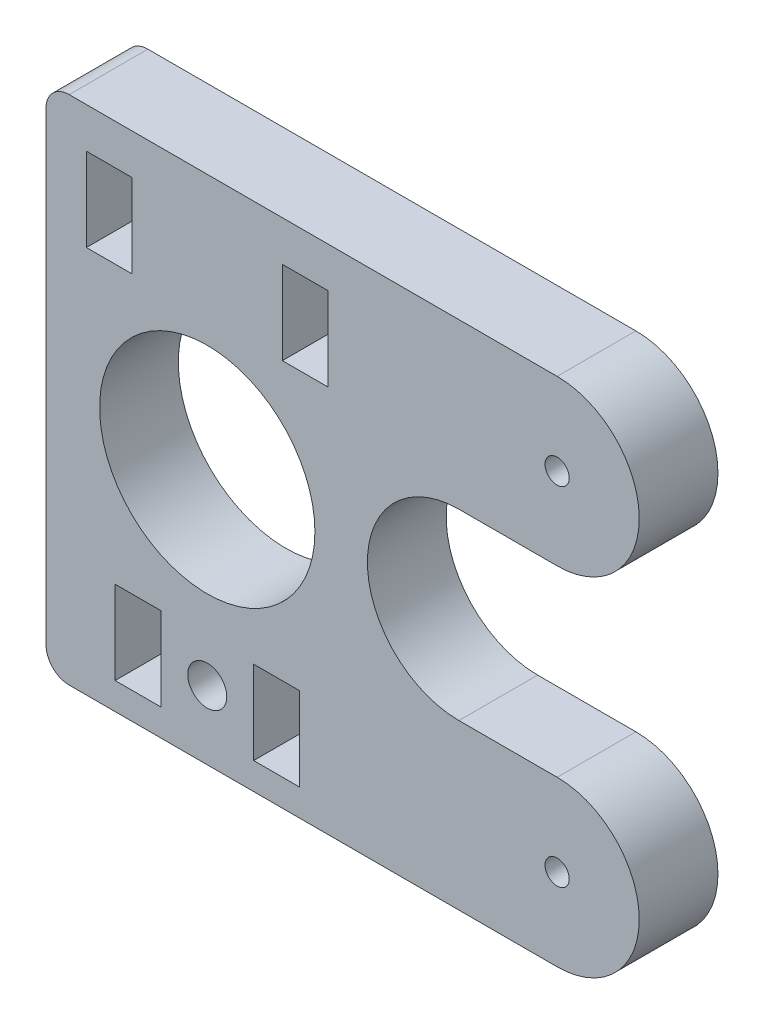
SolidWorks part; units mm, degrees
material "Acrylic (Medium-high impact)"
ref_plane "Front Plane" through (0, 0, 0) normal (0, 0, 1) x (1, 0, 0)
ref_plane "Top Plane" through (0, 0, 0) normal (0, 1, 0) x (1, 0, 0)
ref_plane "Right Plane" through (0, 0, 0) normal (1, 0, 0) x (0, 0, -1)
sketch "Sketch1" plane through (0, 0, 0) normal (0, 0, 1) x (1, 0, 0)
  line L0 (669.2168, 349.7655) -> (648.4638, 349.7655)
  line L1 (646.7465, 348.0482) -> (646.7465, 313.4828)
  line L2 (648.4638, 311.7655) -> (669.2168, 311.7655)
  line L3 (653.1465, 340.5655) -> (653.1465, 346.7655)
  line L4 (653.1465, 346.7655) -> (649.7465, 346.7655)
  line L5 (649.7465, 346.7655) -> (649.7465, 340.5655)
  line L6 (649.7465, 340.5655) -> (653.1465, 340.5655)
  line L7 (651.8765, 313.7655) -> (655.2765, 313.7655)
  line L8 (655.2765, 313.7655) -> (655.2765, 319.9655)
  line L9 (655.2765, 319.9655) -> (651.8765, 319.9655)
  line L10 (651.8765, 319.9655) -> (651.8765, 313.7655)
  line L11 (667.7065, 340.5655) -> (667.7065, 346.7655)
  line L12 (667.7065, 346.7655) -> (664.3065, 346.7655)
  line L13 (664.3065, 346.7655) -> (664.3065, 340.5655)
  line L14 (664.3065, 340.5655) -> (667.7065, 340.5655)
  line L15 (662.1765, 319.9655) -> (662.1765, 313.7655)
  line L16 (662.1765, 313.7655) -> (665.5765, 313.7655)
  line L17 (665.5765, 313.7655) -> (665.5765, 319.9655)
  line L18 (665.5765, 319.9655) -> (662.1765, 319.9655)
  line L19 (-318.4867, 330.7655) -> (49681.5133, 330.7655) construction
  line L21 (653.1465, 340.5655) -> (664.3065, 340.5655) construction
  line L22 (657.2765, 316.8655) -> (655.2765, 316.8655) construction
  line L23 (660.1765, 316.8655) -> (662.1765, 316.8655) construction
  line L24 (658.7265, -666.0306) -> (658.7265, 49333.9694) construction
  line L25 (669.2168, 311.7655) -> (684.7265, 311.7655)
  line L26 (669.2168, 349.7655) -> (684.7265, 349.7655)
  line L27 (684.7265, 317.8655) -> (684.7265, 330.7655) construction
  line L28 (684.7265, 330.7655) -> (684.7265, 343.6655) construction
  line L29 (684.7265, -670.5722) -> (684.7265, 49329.4278) construction
  line L30 (662.1765, 330.7655) -> (662.1765, 349.7655) construction
  line L31 (662.1765, 330.7655) -> (662.1765, 311.7655) construction
  line L32 (684.7265, 337.5655) -> (677.4265, 337.5655)
  line L33 (684.7265, 323.9655) -> (677.4265, 323.9655)
  circle A0 centre (684.7265, 343.6655) radius 0.9
  circle A1 centre (684.7265, 317.8655) radius 0.9
  arc A2 (684.7265, 311.7655) -> (684.7265, 323.9655) centre (684.7265, 317.8655) ccw
  circle A3 centre (658.7265, 316.8655) radius 1.45
  arc A4 (648.4638, 349.7655) -> (646.7465, 348.0482) centre (648.4638, 348.0482) ccw
  arc A5 (684.7265, 349.7655) -> (684.7265, 337.5655) centre (684.7265, 343.6655) cw
  arc A6 (677.4265, 337.5655) -> (677.4265, 323.9655) centre (677.4265, 330.7655) ccw
  arc A7 (646.7465, 313.4828) -> (648.4638, 311.7655) centre (648.4638, 313.4828) ccw
  circle A8 centre (658.7265, 330.7655) radius 8
  point P27 (658.7265, 340.5655)
  point P38 (670.6265, 330.7655)
  point P39 (666.7265, 330.7655)
  dimension "D5" = 2.9
  dimension "D12" = 26
  dimension "D13" = 16
  dimension "D14" = 1.8
  dimension "D15" = 1.7173
  dimension "D1" = 2
  dimension "D2" = 6.2
  dimension "D3" = 3.4
  dimension "D4" = 3.4
  dimension "D6" = 11.16
  dimension "D7" = 3
  dimension "D8" = 3
  dimension "D9" = 2
  dimension "D10" = 33
  dimension "D11" = 12.9
  dimension "D16" = 3.9
extrude "Boss-Extrude2" add sketch "Sketch1" along normal blind 5.85
